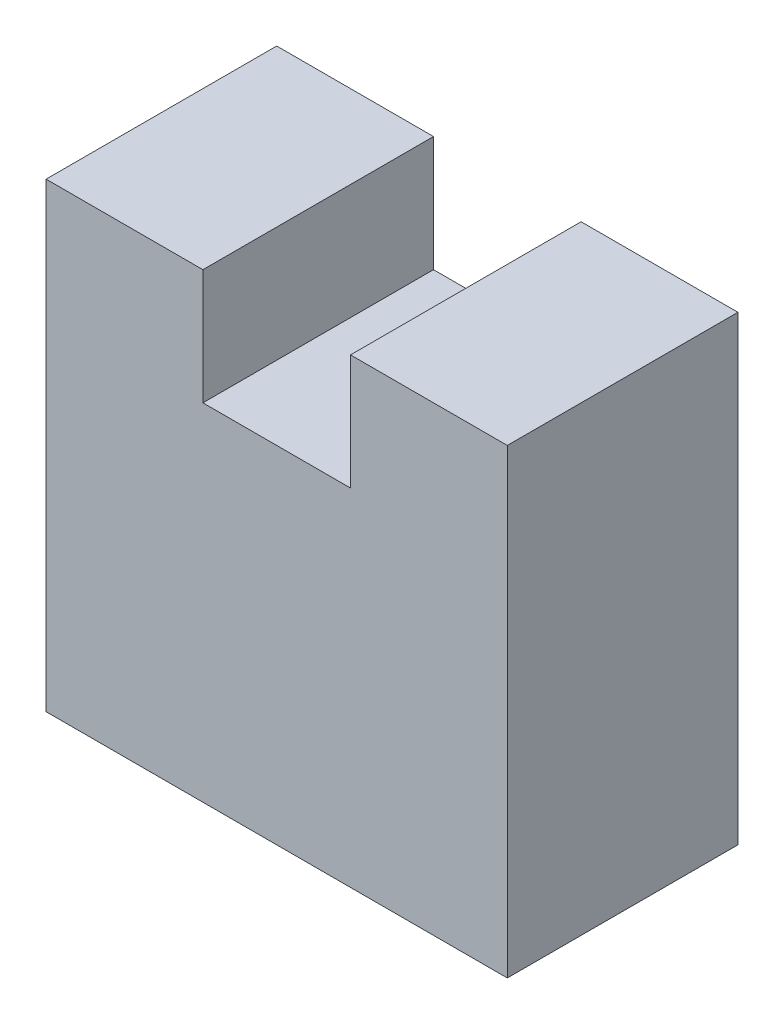
SolidWorks part; units mm, degrees
ref_plane "前视基准面" through (0, 0, 0) normal (0, 0, 1) x (1, 0, 0)
ref_plane "上视基准面" through (0, 0, 0) normal (0, 1, 0) x (1, 0, 0)
ref_plane "右视基准面" through (0, 0, 0) normal (1, 0, 0) x (0, 0, -1)
sketch "草图1" plane through (0, 0, 0) normal (0, 0, 1) x (1, 0, 0)
  line L1 (-10, -10) -> (10, -10)
  line L2 (-10, -10) -> (-10, 10)
  line L3 (-10, 10) -> (10, 10)
  line L4 (10, -10) -> (10, 10)
  line L5 (-10, -10) -> (10, 10) construction
  line L6 (-10, 10) -> (10, -10) construction
  point P0 (0, 0)
extrude "凸台-拉伸1" add sketch "草图1" along normal blind 10
sketch "草图2" plane through (0, 0, 10) normal (0, 0, 1) x (1, 0, 0)
  line L0 (0, 10) -> (3.2, 10)
  line L1 (10, 10) -> (-10, 10) construction
  line L2 (3.2, 10) -> (3.2, 5)
  line L3 (3.2, 5) -> (-3.2, 5)
  line L4 (-3.2, 5) -> (-3.2, 10)
  line L5 (-3.2, 10) -> (0, 10)
  point P7 (0, 0)
  point P8 (0, 0)
  point P9 (0, 0)
  point P10 (0, 0)
extrude "切除-拉伸1" cut sketch "草图2" against normal blind 10
